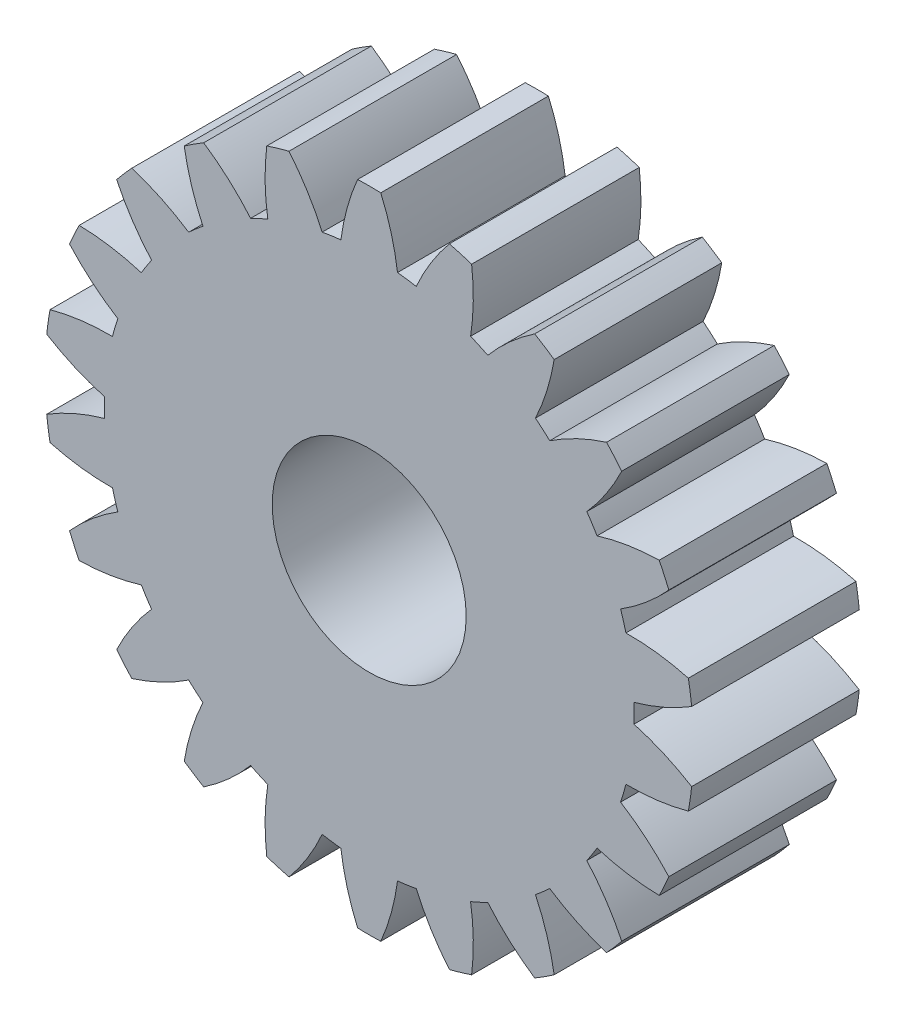
SolidWorks part; units mm, degrees
ref_plane "Front Plane" through (0, 0, 0) normal (0, 0, 1) x (1, 0, 0)
ref_plane "Top Plane" through (0, 0, 0) normal (0, 1, 0) x (1, 0, 0)
ref_plane "Right Plane" through (0, 0, 0) normal (1, 0, 0) x (0, 0, -1)
ref_plane "Plane1" through (0, 0, 6.35) normal (0, 0, 1) x (1, 0, 0)
sketch "Sketch1" plane through (0, 0, 6.35) normal (0, 0, 1) x (1, 0, 0)
  circle A0 centre (0, 0) radius 3.675
  arc A1 (-3.88, 11.6576) -> (-3.8411, 9.2732) centre (4.6954, 10.605) ccw
  arc A2 (-3.8411, 9.2732) -> (-4.4929, 8.9756) centre (0, 0) ccw
  arc A3 (-4.4929, 8.9756) -> (-6.2693, 10.5664) centre (-11.0895, 3.3963) ccw
  arc A4 (-6.2693, 10.5664) -> (-7.0072, 10.0922) centre (0, 0) ccw
  arc A5 (-7.0072, 10.0922) -> (-6.2981, 7.8154) centre (1.5174, 11.4983) ccw
  arc A6 (-6.2981, 7.8154) -> (-6.8396, 7.3462) centre (0, 0) ccw
  arc A7 (-6.8396, 7.3462) -> (-8.9923, 8.3721) centre (-11.5972, 0.1344) ccw
  arc A8 (-8.9923, 8.3721) -> (-9.5666, 7.7093) centre (0, 0) ccw
  arc A9 (-9.5666, 7.7093) -> (-8.2448, 5.7245) centre (-1.7835, 11.46) ccw
  arc A10 (-8.2448, 5.7245) -> (-8.6322, 5.1217) centre (0, 0) ccw
  arc A11 (-8.6322, 5.1217) -> (-10.9867, 5.4996) centre (-11.1653, -3.1383) ccw
  arc A12 (-10.9867, 5.4996) -> (-11.3511, 4.7018) centre (0, 0) ccw
  arc A13 (-11.3511, 4.7018) -> (-9.5236, 3.1698) centre (-4.9399, 10.4933) ccw
  arc A14 (-9.5236, 3.1698) -> (-9.7255, 2.4823) centre (0, 0) ccw
  arc A15 (-9.7255, 2.4823) -> (-12.0911, 2.1815) centre (-9.8288, -6.1568) ccw
  arc A16 (-12.0911, 2.1815) -> (-12.2159, 1.3133) centre (0, 0) ccw
  arc A17 (-12.2159, 1.3133) -> (-10.0309, 0.3583) centre (-7.6961, 8.6765) ccw
  arc A18 (-10.0309, 0.3583) -> (-10.0309, -0.3583) centre (0, 0) ccw
  arc A19 (-10.0309, -0.3583) -> (-12.2159, -1.3133) centre (-7.6961, -8.6765) ccw
  arc A20 (-12.2159, -1.3133) -> (-12.0911, -2.1815) centre (0, 0) ccw
  arc A21 (-12.0911, -2.1815) -> (-9.7255, -2.4823) centre (-9.8288, 6.1568) ccw
  arc A22 (-9.7255, -2.4823) -> (-9.5236, -3.1698) centre (0, 0) ccw
  arc A23 (-9.5236, -3.1698) -> (-11.3511, -4.7018) centre (-4.9399, -10.4933) ccw
  arc A24 (-11.3511, -4.7018) -> (-10.9867, -5.4996) centre (0, 0) ccw
  arc A25 (-10.9867, -5.4996) -> (-8.6322, -5.1217) centre (-11.1653, 3.1383) ccw
  arc A26 (-8.6322, -5.1217) -> (-8.2448, -5.7245) centre (0, 0) ccw
  arc A27 (-8.2448, -5.7245) -> (-9.5666, -7.7093) centre (-1.7835, -11.46) ccw
  arc A28 (-9.5666, -7.7093) -> (-8.9923, -8.3721) centre (0, 0) ccw
  arc A29 (-8.9923, -8.3721) -> (-6.8396, -7.3462) centre (-11.5972, -0.1344) ccw
  arc A30 (-6.8396, -7.3462) -> (-6.2981, -7.8154) centre (0, 0) ccw
  arc A31 (-6.2981, -7.8154) -> (-7.0072, -10.0922) centre (1.5174, -11.4983) ccw
  arc A32 (-7.0072, -10.0922) -> (-6.2693, -10.5664) centre (0, 0) ccw
  arc A33 (-6.2693, -10.5664) -> (-4.4929, -8.9756) centre (-11.0895, -3.3963) ccw
  arc A34 (-4.4929, -8.9756) -> (-3.8411, -9.2732) centre (0, 0) ccw
  arc A35 (-3.8411, -9.2732) -> (-3.88, -11.6576) centre (4.6954, -10.605) ccw
  arc A36 (-3.88, -11.6576) -> (-3.0385, -11.9047) centre (0, 0) ccw
  arc A37 (-3.0385, -11.9047) -> (-1.7822, -9.8778) centre (-9.6835, -6.383) ccw
  arc A38 (-1.7822, -9.8778) -> (-1.0729, -9.9798) centre (0, 0) ccw
  arc A39 (-1.0729, -9.9798) -> (-0.4385, -12.2785) centre (7.493, -8.8526) ccw
  arc A40 (-0.4385, -12.2785) -> (0.4385, -12.2785) centre (0, 0) ccw
  arc A41 (0.4385, -12.2785) -> (1.0729, -9.9798) centre (-7.493, -8.8526) ccw
  arc A42 (1.0729, -9.9798) -> (1.7822, -9.8778) centre (0, 0) ccw
  arc A43 (1.7822, -9.8778) -> (3.0385, -11.9047) centre (9.6835, -6.383) ccw
  arc A44 (3.0385, -11.9047) -> (3.88, -11.6576) centre (0, 0) ccw
  arc A45 (3.88, -11.6576) -> (3.8411, -9.2732) centre (-4.6954, -10.605) ccw
  arc A46 (3.8411, -9.2732) -> (4.4929, -8.9756) centre (0, 0) ccw
  arc A47 (4.4929, -8.9756) -> (6.2693, -10.5664) centre (11.0895, -3.3963) ccw
  arc A48 (6.2693, -10.5664) -> (7.0072, -10.0922) centre (0, 0) ccw
  arc A49 (7.0072, -10.0922) -> (6.2981, -7.8154) centre (-1.5174, -11.4983) ccw
  arc A50 (6.2981, -7.8154) -> (6.8396, -7.3462) centre (0, 0) ccw
  arc A51 (6.8396, -7.3462) -> (8.9923, -8.3721) centre (11.5972, -0.1344) ccw
  arc A52 (8.9923, -8.3721) -> (9.5666, -7.7093) centre (0, 0) ccw
  arc A53 (9.5666, -7.7093) -> (8.2448, -5.7245) centre (1.7835, -11.46) ccw
  arc A54 (8.2448, -5.7245) -> (8.6322, -5.1217) centre (0, 0) ccw
  arc A55 (8.6322, -5.1217) -> (10.9867, -5.4996) centre (11.1653, 3.1383) ccw
  arc A56 (10.9867, -5.4996) -> (11.3511, -4.7018) centre (0, 0) ccw
  arc A57 (11.3511, -4.7018) -> (9.5236, -3.1698) centre (4.9399, -10.4933) ccw
  arc A58 (9.5236, -3.1698) -> (9.7255, -2.4823) centre (0, 0) ccw
  arc A59 (9.7255, -2.4823) -> (12.0911, -2.1815) centre (9.8288, 6.1568) ccw
  arc A60 (12.0911, -2.1815) -> (12.2159, -1.3133) centre (0, 0) ccw
  arc A61 (12.2159, -1.3133) -> (10.0309, -0.3583) centre (7.6961, -8.6765) ccw
  arc A62 (10.0309, -0.3583) -> (10.0309, 0.3583) centre (0, 0) ccw
  arc A63 (10.0309, 0.3583) -> (12.2159, 1.3133) centre (7.6961, 8.6765) ccw
  arc A64 (12.2159, 1.3133) -> (12.0911, 2.1815) centre (0, 0) ccw
  arc A65 (12.0911, 2.1815) -> (9.7255, 2.4823) centre (9.8288, -6.1568) ccw
  arc A66 (9.7255, 2.4823) -> (9.5236, 3.1698) centre (0, 0) ccw
  arc A67 (9.5236, 3.1698) -> (11.3511, 4.7018) centre (4.9399, 10.4933) ccw
  arc A68 (11.3511, 4.7018) -> (10.9867, 5.4996) centre (0, 0) ccw
  arc A69 (10.9867, 5.4996) -> (8.6322, 5.1217) centre (11.1653, -3.1383) ccw
  arc A70 (8.6322, 5.1217) -> (8.2448, 5.7245) centre (0, 0) ccw
  arc A71 (8.2448, 5.7245) -> (9.5666, 7.7093) centre (1.7835, 11.46) ccw
  arc A72 (9.5666, 7.7093) -> (8.9923, 8.3721) centre (0, 0) ccw
  arc A73 (8.9923, 8.3721) -> (6.8396, 7.3462) centre (11.5972, 0.1344) ccw
  arc A74 (6.8396, 7.3462) -> (6.2981, 7.8154) centre (0, 0) ccw
  arc A75 (6.2981, 7.8154) -> (7.0072, 10.0922) centre (-1.5174, 11.4983) ccw
  arc A76 (7.0072, 10.0922) -> (6.2693, 10.5664) centre (0, 0) ccw
  arc A77 (6.2693, 10.5664) -> (4.4929, 8.9756) centre (11.0895, 3.3963) ccw
  arc A78 (4.4929, 8.9756) -> (3.8411, 9.2732) centre (0, 0) ccw
  arc A79 (3.8411, 9.2732) -> (3.88, 11.6576) centre (-4.6954, 10.605) ccw
  arc A80 (3.88, 11.6576) -> (3.0385, 11.9047) centre (0, 0) ccw
  arc A81 (3.0385, 11.9047) -> (1.7822, 9.8778) centre (9.6835, 6.383) ccw
  arc A82 (1.7822, 9.8778) -> (1.0729, 9.9798) centre (0, 0) ccw
  arc A83 (1.0729, 9.9798) -> (0.4385, 12.2785) centre (-7.493, 8.8526) ccw
  arc A84 (0.4385, 12.2785) -> (-0.4385, 12.2785) centre (0, 0) ccw
  arc A85 (-0.4385, 12.2785) -> (-1.0729, 9.9798) centre (7.493, 8.8526) ccw
  arc A86 (-1.0729, 9.9798) -> (-1.7822, 9.8778) centre (0, 0) ccw
  arc A87 (-1.7822, 9.8778) -> (-3.0385, 11.9047) centre (-9.6835, 6.383) ccw
  arc A88 (-3.0385, 11.9047) -> (-3.88, 11.6576) centre (0, 0) ccw
extrude "Boss-Extrude1" add sketch "Sketch1" against normal blind 6.35
